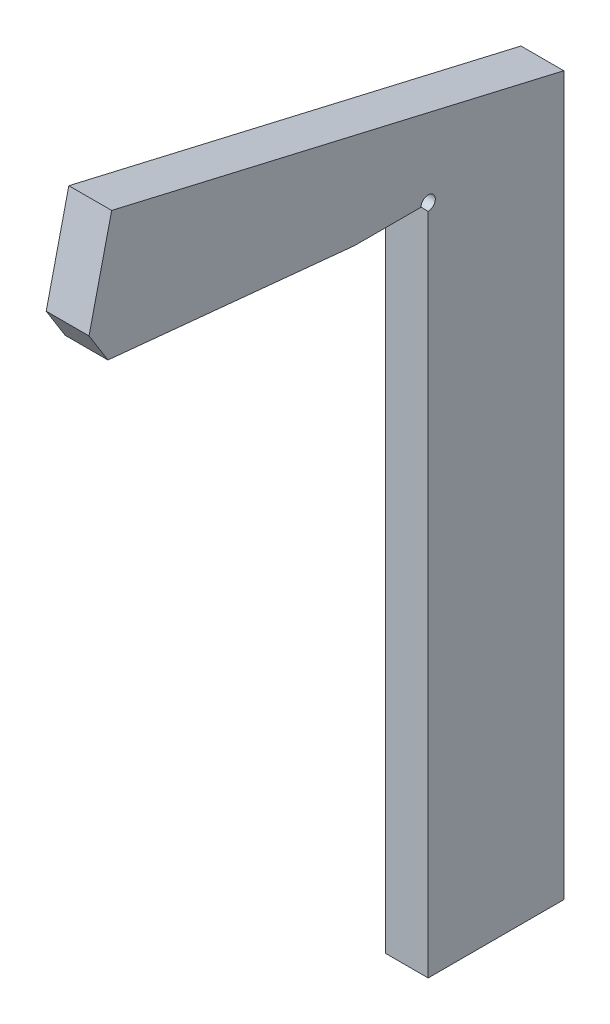
SolidWorks part; units mm, degrees
material "MDF"
ref_plane "Front Plane" through (0, 0, 0) normal (0, 0, 1) x (1, 0, 0)
ref_plane "Top Plane" through (0, 0, 0) normal (0, 1, 0) x (1, 0, 0)
ref_plane "Right Plane" through (0, 0, 0) normal (1, 0, 0) x (0, 0, -1)
sketch "Sketch2" plane through (-113.7888, 0, 0) normal (1, 0, 0) x (0, 0, -1)
  line L17 (0, 20.8246) -> (-83.8286, 40.3069)
  line L18 (0, 20.8246) -> (-83.8286, 40.3069)
  line L29 (-83.8286, 40.3069) -> (-93.1962, 0)
  line L30 (-83.8286, 40.3069) -> (-93.1962, 0)
  line L31 (-93.1962, 0) -> (-63.5, 0)
  line L32 (-93.1962, 0) -> (-63.5, 0)
  line L46 (0, -298.45) -> (-60.325, -298.45)
  line L47 (0, -363.22) -> (0, -433.07) construction
  line L48 (-28.575, -298.45) -> (0, -298.45) construction
  line L53 (-28.575, -447.675) -> (-28.575, -450.85)
  line L54 (-28.575, -450.85) -> (0, -450.85)
  line L55 (0, -450.85) -> (0, 20.8246)
  line L57 (-60.325, -3.175) -> (-60.325, -412.75)
  line L60 (0, -298.45) -> (0, 20.8246)
  line L62 (-60.325, -3.175) -> (-60.325, -298.45)
  arc A14 (-60.325, -3.175) -> (-63.5, 0) centre (-60.325, 0) ccw
  arc A15 (-60.325, -412.75) -> (-31.746, -444.3413) centre (-28.575, -412.75) ccw
  arc A16 (-28.575, -447.675) -> (-31.746, -444.3413) centre (-28.575, -444.5) ccw
  arc A17 (-60.325, -3.175) -> (-63.5, 0) centre (-60.325, 0) ccw
  dimension "D2" = 0
extrude "Boss-Extrude1" add sketch "Sketch2" along normal blind 19.05
sketch "Sketch3" plane through (-113.7888, 0, 0) normal (-1, 0, 0) x (0, 0, 1)
  line L0 (83.8286, 40.3069) -> (201.0857, 67.5582)
  line L1 (495.3358, 135.9439) -> (66.675, 36.3203) construction
  line L2 (201.0857, 67.5582) -> (214.0229, 11.8918)
  line L7 (83.8286, 40.3069) -> (93.1962, 0)
  line L8 (93.1962, 0) -> (214.0229, 11.8918)
  arc A0 (63.5, 0) -> (60.325, -3.175) centre (60.325, 0) ccw construction
  dimension "D1" = 57.15
  dimension "D2" = 152.4
extrude "Boss-Extrude2" add sketch "Sketch3" against normal through all
chamfer "Chamfer1" distance 12.7 angle 45 1 edges at (-104.2638, 11.8918, 214.0229)
